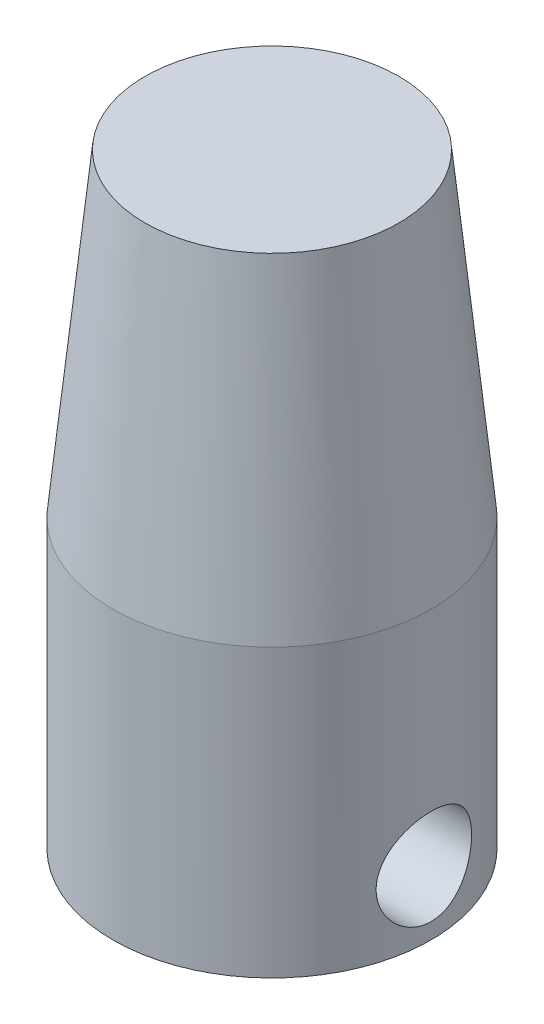
SolidWorks part; units mm, degrees
ref_plane "Front Plane" through (0, 0, 0) normal (0, 0, 1) x (1, 0, 0)
ref_plane "Top Plane" through (0, 0, 0) normal (0, 1, 0) x (1, 0, 0)
ref_plane "Right Plane" through (0, 0, 0) normal (1, 0, 0) x (0, 0, -1)
sketch "Sketch1" plane through (0, 0, 0) normal (0, 1, 0) x (1, 0, 0)
  circle A0 centre (0, 0) radius 5
  dimension "D1" = 10
extrude "body" add sketch "Sketch1" along normal blind 9
sketch "Sketch2" plane through (0, 0, 0) normal (1, 0, 0) x (0, 0, -1)
  circle A0 centre (0, 2) radius 1.5
  dimension "D1" = 2
  dimension "D2" = 3
extrude "pin insert" cut sketch "Sketch2" against normal through all and the other way through all
ref_plane "contact plane" through (0, 19, 0) normal (0, 1, 0) x (1, 0, 0)
sketch "head SA" plane through (0, 19, 0) normal (0, 1, 0) x (1, 0, 0)
  circle A0 centre (0, 0) radius 3.989
  dimension "D1" = 7.978
loft "cone" add profiles "head SA" section "head SA" section face at (0, 9, 5)
